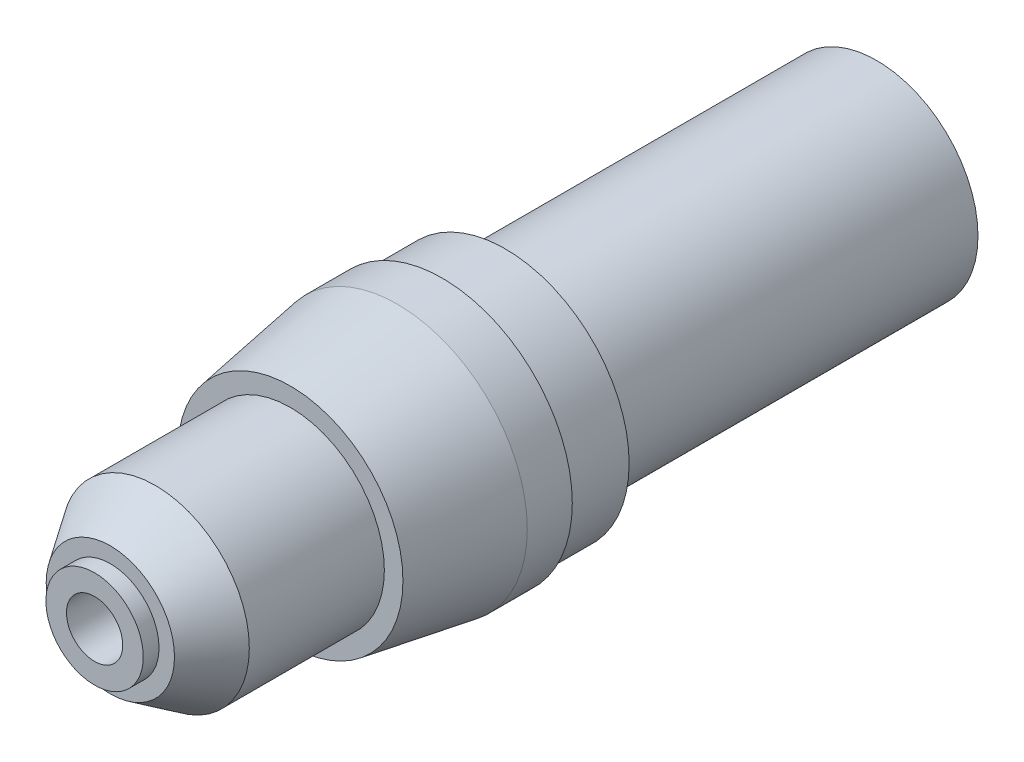
SolidWorks part; units mm, degrees
ref_plane "Front Plane" through (0, 0, 0) normal (0, 0, 1) x (1, 0, 0)
ref_plane "Top Plane" through (0, 0, 0) normal (0, 1, 0) x (1, 0, 0)
ref_plane "Right Plane" through (0, 0, 0) normal (1, 0, 0) x (0, 0, -1)
sketch "Sketch2" plane through (0, 0, 0) normal (0, 0, 1) x (1, 0, 0)
  circle A0 centre (0, 0) radius 22.86
  dimension "D1" = 45.72
extrude "Boss-Extrude1" add sketch "Sketch2" along normal blind 83.82
sketch "Sketch3" plane through (0, 0, 83.82) normal (0, 0, 1) x (1, 0, 0)
  circle A0 centre (0, 0) radius 27.94
  dimension "D1" = 55.88
extrude "Boss-Extrude2" add sketch "Sketch3" along normal blind 14.224
sketch "Sketch4" plane through (0, 0, 0) normal (0, 0, -1) x (-1, 0, 0)
  circle A0 centre (0, 0) radius 7.493
  dimension "D1" = 14.986
extrude "Boss-Extrude3" add sketch "Sketch4" along normal blind 4.445
sketch "Sketch5" plane through (0, 0, 98.044) normal (0, 0, 1) x (1, 0, 0)
  circle A0 centre (0, 0) radius 29.337
  dimension "D1" = 58.674
extrude "Boss-Extrude4" add sketch "Sketch5" along normal blind 10.16
sketch "Sketch6" plane through (0, 0, 108.204) normal (0, 0, 1) x (1, 0, 0)
  circle A0 centre (0, 0) radius 25.4
  dimension "D1" = 50.8
extrude "Boss-Extrude5" add sketch "Sketch6" along normal blind 24.13
loft "Loft1" add section edge at (29.337, 0, 108.204) section edge at (25.4, 0, 132.334)
sketch "Sketch7" plane through (0, 0, 132.334) normal (0, 0, 1) x (1, 0, 0)
  circle A0 centre (0, 0) radius 21.209
  dimension "D1" = 42.418
extrude "Boss-Extrude6" add sketch "Sketch7" along normal blind 30.48
sketch "Sketch8" plane through (0, 0, 162.814) normal (0, 0, 1) x (1, 0, 0)
  circle A0 centre (0, 0) radius 14.478
  dimension "D1" = 28.956
extrude "Boss-Extrude7" add sketch "Sketch8" along normal blind 10.16
sketch "Sketch9" plane through (0, 0, 172.974) normal (0, 0, 1) x (1, 0, 0)
  circle A0 centre (0, 0) radius 10.9855
  dimension "D1" = 21.971
extrude "Boss-Extrude8" add sketch "Sketch9" along normal blind 3.556
loft "Loft2" add section edge at (21.209, 0, 162.814) section edge at (14.478, 0, 172.974)
sketch "Sketch10" plane through (0, 0, 176.53) normal (0, 0, 1) x (1, 0, 0)
  circle A0 centre (0, 0) radius 6.35
  dimension "D1" = 12.7
extrude "Cut-Extrude1" cut sketch "Sketch10" against normal blind 25.4
